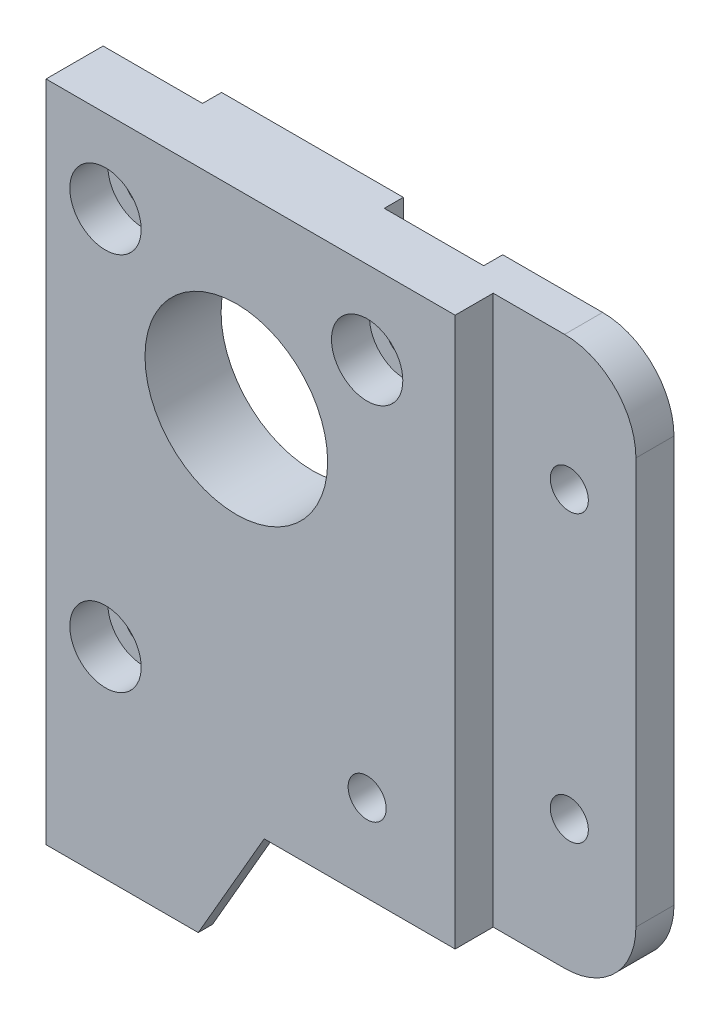
SolidWorks part; units mm, degrees
material "Onyx"
ref_plane "Front Plane" through (0, 0, 0) normal (0, 0, 1) x (1, 0, 0)
ref_plane "Top Plane" through (0, 0, 0) normal (0, 1, 0) x (1, 0, 0)
ref_plane "Right Plane" through (0, 0, 0) normal (1, 0, 0) x (0, 0, -1)
sketch "Sketch1" plane through (0, 0, 0) normal (0, 0, 1) x (1, 0, 0)
  line L0 (-13.75, -19.7) -> (-9.788, -16.65) construction
  line L3 (20, 28.85) -> (38, 28.85)
  line L8 (20, -28.85) -> (-20, -28.85)
  line L9 (20, -28.85) -> (20, 28.85) construction
  line L10 (38, 28.85) -> (38, -28.85)
  line L11 (20, 28.85) -> (-20, 28.85)
  line L14 (-20, -28.85) -> (-20, 28.85)
  line L15 (20, -28.85) -> (-20, 28.85) construction
  line L16 (20, 28.85) -> (-20, -28.85) construction
  line L17 (-16.312, -16.3719) -> (-12.35, -13.3219)
  line L18 (-11.188, -23.0281) -> (-7.226, -19.9781)
  line L19 (0, -28.85) -> (0, 28.85) construction
  line L22 (38, -28.85) -> (20, -28.85)
  line L23 (17.2017, -17.3071) -> (20, -21.3437)
  line L24 (9.55, -19.7) -> (9.55, -28.85)
  line L25 (-9.55, 20.15) -> (-9.55, 28.85)
  line L26 (-17.2017, 17.7571) -> (-20, 21.7937)
  line L27 (9.55, 20.15) -> (9.55, 28.85)
  line L28 (17.2017, 17.7571) -> (20, 21.7937)
  line L29 (20, 21.7937) -> (20, 28.85)
  line L30 (-16.312, -16.3719) -> (-20, -16.3719)
  line L31 (20, -28.85) -> (20, -21.3437)
  line L33 (-13.75, -23.9) -> (-13.75, -28.85)
  circle A18 centre (-13.75, 20.15) radius 4.2
  circle A19 centre (13.75, 20.15) radius 4.2
  circle A20 centre (13.75, -19.7) radius 4.2
  arc A21 (-16.312, -16.3719) -> (-11.188, -23.0281) centre (-13.75, -19.7) ccw
  arc A22 (-7.226, -19.9781) -> (-12.35, -13.3219) centre (-9.788, -16.65) ccw
  circle A23 centre (0, 8.8) radius 9.6
  circle A24 centre (-5.725, -6.1) radius 4.2
  circle A25 centre (5.725, -6.1) radius 4.2
  point P0 (0, 0)
  point P14 (-6.4599, -14.088)
  point P31 (-11.769, -18.175)
  point P37 (5.725, -10.3)
  point P43 (20, 28.85)
  point P46 (-20, 28.85)
  dimension "D1" = 57.7
  dimension "D2" = 40
  dimension "D3" = 12.2
  dimension "D4" = 8.4
  dimension "D5" = 8.4
  dimension "D6" = 19.2
  dimension "D7" = 9.15
  dimension "D8" = 27.5
  dimension "D9" = 39.85
  dimension "D10" = 5
  dimension "D12" = 20.05
  dimension "D13" = 11.45
  dimension "D14" = 22.75
  dimension "D15" = 18
extrude "Boss-Extrude1" add sketch "Sketch1" along normal blind 2
sketch "Sketch4" plane through (0, 0, 2) normal (0, 0, 1) x (1, 0, 0)
  line L0 (0, -28.85) -> (0, 29) construction
  line L6 (38, -28.85) -> (20, -28.85) construction
  line L8 (-20, -28.85) -> (38, -28.85)
  line L11 (38, -28.85) -> (38, 28.85)
  line L12 (-20, 28.85) -> (-20, -28.85)
  line L13 (-20, -16.3719) -> (-20, 21.7937) construction
  line L14 (-20, 28.85) -> (38, 28.85)
  line L15 (20, 28.85) -> (38, 28.85) construction
  line L16 (38, 28.85) -> (38, -28.85) construction
  circle A2 centre (13.75, -19.7) radius 2
  circle A3 centre (-13.75, 20.15) radius 2
  circle A4 centre (13.75, 20.15) radius 2
  circle A10 centre (-13.75, -19.7) radius 2
  circle A11 centre (0, 8.8) radius 9.6
  circle A12 centre (0, 8.8) radius 9.6 construction
  dimension "D1" = 4
extrude "Boss-Extrude3" add sketch "Sketch4" along normal blind 2
sketch "Sketch5" plane through (0, 0, 4) normal (0, 0, 1) x (1, 0, 0)
  line L0 (-20, 0) -> (38, 0) construction
  line L3 (-20, 28.85) -> (-20, -28.85) construction
  line L4 (38, -28.85) -> (38, 28.85) construction
  circle A0 centre (31, 15) radius 2
  circle A1 centre (31, -15) radius 2
  dimension "D1" = 4
  dimension "D2" = 15
  dimension "D3" = 51
extrude "Cut-Extrude1" cut sketch "Sketch5" against normal blind 4
ref_plane "Plane1" through (0, 0, 0) normal (0, 0, -1) x (-1, 0, 0)
sketch "Sketch6" plane through (0, 0, 4) normal (0, 0, 1) x (1, 0, 0)
  line L0 (23, 28.85) -> (23, -28.85)
  line L1 (38, 28.85) -> (-20, 28.85) construction
  line L2 (-20, -28.85) -> (38, -28.85) construction
  line L3 (38, -28.85) -> (38, 28.85) construction
  circle A52 centre (-13.75, 20.15) radius 3.75
  circle A53 centre (13.75, 20.15) radius 3.75
  circle A54 centre (31, 15) radius 2
  circle A55 centre (13.75, -19.7) radius 3.75
  circle A56 centre (-13.75, -19.7) radius 3.75
  circle A57 centre (31, -15) radius 2
  circle A59 centre (31, 15) radius 2 construction
  circle A60 centre (31, -15) radius 2 construction
  line M5 (-20, 28.85) -> (-20, -28.85)
  line M6 (-20, -28.85) -> (38, -28.85)
  line M7 (38, -28.85) -> (38, 28.85)
  line M8 (38, 28.85) -> (-20, 28.85)
  circle M9 centre (13.75, -19.7) radius 2
  circle M11 centre (0, 8.8) radius 9.6
  dimension "D1" = 7.5
  dimension "D2" = 15
extrude "Boss-Extrude4" add sketch "Sketch6" along normal blind 4 contours A57 A56 A55 A54 A53 A52 M8 M5 M6 M7 M11 | A55 M9
sketch "Sketch7" plane through (0, 0, 4) normal (0, 0, 1) x (1, 0, 0)
  line L0 (38, -28.85) -> (38, 28.85) construction
  line L1 (30.5, 28.85) -> (38, 28.85)
  line L2 (38, 28.85) -> (38, 21.35)
  line L3 (-20, 0) -> (38, 0) construction
  line L4 (-20, 28.85) -> (-20, -28.85) construction
  line L5 (38, -28.85) -> (38, -21.35)
  line L6 (30.5, -28.85) -> (38, -28.85)
  arc A0 (38, 21.35) -> (30.5, 28.85) centre (30.5, 21.35) ccw
  arc A1 (38, -21.35) -> (30.5, -28.85) centre (30.5, -21.35) cw
  dimension "D1" = 15
extrude "Cut-Extrude2" cut sketch "Sketch7" against normal through all
sketch "Sketch9" plane through (-20, 0, 0) normal (-1, 0, 0) x (0, 0, 1)
  line L0 (8, -28.85) -> (8, -40.85)
  line L2 (8, -40.85) -> (0, -40.85)
  line L3 (0, -40.85) -> (0, -35.15)
  line L4 (0, -35.15) -> (2, -35.15)
  line L5 (2, -35.15) -> (2, -28.85)
  line L6 (8, -28.85) -> (2, -28.85) construction
  line L7 (0, -16.3719) -> (0, 21.7937) construction
  line L9 (2, -28.85) -> (8, -28.85)
  dimension "D1" = 6
  dimension "D2" = 12
  dimension "D3" = 6.3
extrude "Boss-Extrude5" add sketch "Sketch9" against normal blind 6
sketch "Sketch10" plane through (0, 0, 8) normal (0, 0, 1) x (1, 0, 0)
  line L0 (-14, -40.85) -> (-4, -40.85)
  line L1 (-4, -40.85) -> (2.9282, -28.85)
  line L3 (2.9282, -28.85) -> (-14, -28.85)
  line L4 (-14, -28.85) -> (-14, -40.85)
  dimension "D1" = 10
  dimension "D2" = 120
extrude "Boss-Extrude6" add sketch "Sketch10" against normal blind 1.5
